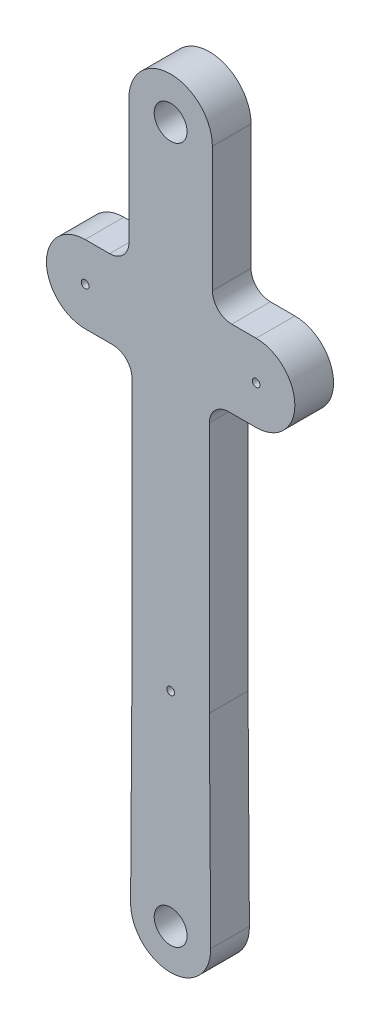
SolidWorks part; units mm, degrees
ref_plane "Front Plane" through (0, 0, 0) normal (0, 0, 1) x (1, 0, 0)
ref_plane "Top Plane" through (0, 0, 0) normal (0, 1, 0) x (1, 0, 0)
ref_plane "Right Plane" through (0, 0, 0) normal (1, 0, 0) x (0, 0, -1)
sketch "Sketch1" plane through (0, 0, 0) normal (0, 0, 1) x (1, 0, 0)
  line L0 (0, 0) -> (0, -80) construction
  line L1 (-22.1, 0) -> (22.1, 0) construction
  line L2 (-22.1, 0) -> (22.1, 0) construction
  line L3 (-22.1, 10) -> (-10.7829, 10)
  line L4 (-22.1, -10) -> (-10, -10)
  line L5 (-10, -80) -> (-10, -10)
  line L6 (10, -80) -> (10, -10)
  line L7 (10, -10) -> (22.1, -10)
  line L8 (-10.7829, 47.3123) -> (-10.7829, 10)
  line L9 (10.7829, 47.3123) -> (10.7829, 10)
  line L10 (-10.3529, -132.5309) -> (-10, -80)
  line L11 (10.3529, -132.5309) -> (10, -80)
  line L12 (10.7829, 10) -> (22.1, 10)
  line L14 (-59.5551, -112) -> (59.5551, -112) construction
  line L15 (-59.5551, -112) -> (-59.5551, 24) construction
  line L16 (-59.5551, 24) -> (59.5551, 24) construction
  line L17 (59.5551, -112) -> (59.5551, 24) construction
  line L18 (-59.5551, -112) -> (59.5551, 24) construction
  line L19 (-59.5551, 24) -> (59.5551, -112) construction
  circle A0 centre (-22.1, 0) radius 1
  circle A1 centre (22.1, 0) radius 1
  circle A2 centre (0, -80) radius 1
  arc A3 (-22.1, 10) -> (-22.1, -10) centre (-22.1, 0) ccw
  arc A4 (22.1, -10) -> (22.1, 10) centre (22.1, 0) ccw
  circle A6 centre (0, 47.3123) radius 4.25
  circle A7 centre (0, -132.6877) radius 4.25
  arc A8 (10.7829, 47.3123) -> (-10.7829, 47.3123) centre (0, 47.3123) ccw
  arc A9 (-10.3529, -132.5309) -> (10.3529, -132.5309) centre (0, -132.6877) ccw
  point P8 (0, 0)
  point P22 (0, -132.5309)
  point P27 (0, -44)
  dimension "D3" = 2
  dimension "D4" = 2
  dimension "D5" = 2
  dimension "D7" = 10
  dimension "D9" = 8.5
  dimension "D10" = 8.5
  dimension "D1" = 44.2
  dimension "D2" = 80
  dimension "D6" = 22.1
  dimension "D11" = 180
  dimension "D8" = 136
  dimension "D12" = 112
extrude "Boss-Extrude1" add sketch "Sketch1" along normal blind 10
fillet "Fillet1" radius 5 4 edges at (-10.7829, 10, 5) (-10, -10, 5) (10, -10, 5) (10.7829, 10, 5)
equation "\"D4@Sketch1\"=\"D3@Sketch1\""
equation "\"D5@Sketch1\"=\"D3@Sketch1\""
equation "\"D6@Sketch1\"=\"D1@Sketch1\"/2"
equation "\"D10@Sketch1\"=\"D9@Sketch1\""
